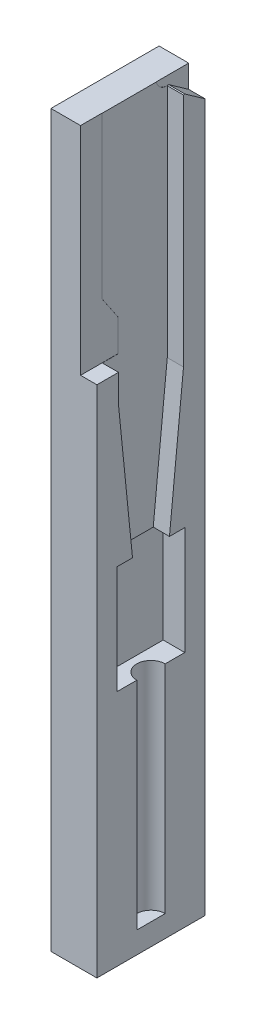
SolidWorks part; units mm, degrees
ref_plane "정면" through (0, 0, 0) normal (0, 0, 1) x (1, 0, 0)
ref_plane "윗면" through (0, 0, 0) normal (0, 1, 0) x (1, 0, 0)
ref_plane "우측면" through (0, 0, 0) normal (1, 0, 0) x (0, 0, -1)
sketch "스케치1" plane through (0, 0, 0) normal (1, 0, 0) x (0, 0, -1)
  line L0 (0, -135) -> (0, 0) construction
  line L1 (-20, -270) -> (20, -270)
  line L2 (-20, -270) -> (-20, 0)
  line L3 (-20, 0) -> (20, 0)
  line L4 (20, -270) -> (20, 0)
  line L5 (-20, -270) -> (20, 0) construction
  line L6 (-20, 0) -> (20, -270) construction
  point P0 (0, -135)
  dimension "D1" = 270
  dimension "D2" = 40
extrude "보스-돌출1" add sketch "스케치1" along normal mid plane 34
sketch "스케치2" plane through (0, 0, 0) normal (1, 0, 0) x (0, 0, -1)
  line L0 (-12.025, 0) -> (-12.025, -90.3198)
  line L1 (20, 0) -> (-20, 0) construction
  line L2 (-12.025, -90.3198) -> (-6, -150.3198)
  line L3 (-6, -150.3198) -> (6, -150.3198)
  line L4 (12.025, -90.3198) -> (6, -150.3198)
  line L5 (12.025, 0) -> (-12.025, 0)
  line L6 (0, 0) -> (0, -150.3198) construction
  line L7 (12.025, 0) -> (12.025, -90.3198)
  dimension "D1" = 12
  dimension "D2" = 24.05
  dimension "D3" = 60
extrude "컷-돌출1" cut sketch "스케치2" against normal mid plane 12
sketch "스케치3" plane through (0, 0, 0) normal (1, 0, 0) x (0, 0, -1)
  line L1 (-66.334, 26.0969) -> (85.9402, 26.0969)
  line L2 (-66.334, 26.0969) -> (-66.334, -328.7738)
  line L3 (-66.334, -328.7738) -> (85.9402, -328.7738)
  line L4 (85.9402, 26.0969) -> (85.9402, -328.7738)
extrude "컷-돌출2" cut sketch "스케치3" along normal through all contours L1 L4 L3 L2
ref_plane "평면1" through (0, -142, 0) normal (0, 1, 0) x (1, 0, 0)
sketch "스케치5" plane through (0, -142, 0) normal (0, 1, 0) x (1, 0, 0)
  line L1 (8, -12.5) -> (-8, -12.5)
  line L2 (8, -12.5) -> (8, 12.5)
  line L3 (8, 12.5) -> (-8, 12.5)
  line L4 (-8, -12.5) -> (-8, 12.5)
  line L5 (8, -12.5) -> (-8, 12.5) construction
  line L6 (8, 12.5) -> (-8, -12.5) construction
  point P0 (0, 0)
  dimension "D1" = 16
  dimension "D2" = 25
extrude "컷-돌출3" cut sketch "스케치5" against normal blind 40
sketch "스케치6" plane through (0, -142, 0) normal (0, 1, 0) x (1, 0, 0)
  circle A0 centre (0, 0) radius 5.25
  dimension "D1" = 10.5
extrude "컷-돌출4" cut sketch "스케치6" against normal blind 120
sketch "스케치7" plane through (0, 0, 0) normal (1, 0, 0) x (0, 0, -1)
  line L0 (-6.1559, -80) -> (-36.7141, -80)
  line L1 (-36.7141, -80) -> (-36.7141, 2.0427)
  line L2 (-36.7141, 2.0427) -> (-12.025, 2.0427)
  line L3 (-6.1559, -68.262) -> (-6.1559, -80)
  line L4 (-12.025, 2.0427) -> (-12.025, -59.5336)
  line L5 (-12.025, -90.3198) -> (-12.025, 0) construction
  line L6 (-12.025, -59.5336) -> (-6.1559, -68.262)
  line L7 (6.8907, 1.9547) -> (7.8972, 1.1819)
  line L8 (24.7897, -11.7879) -> (24.7897, 1.9547)
  line L9 (24.7897, 1.9547) -> (6.8907, 1.9547)
  line L10 (12.5764, -3.1721) -> (24.7897, -11.7879)
  arc A0 (7.8972, 1.1819) -> (12.5764, -3.1721) centre (11.9403, 0.8356) ccw
  dimension "D1" = 80
extrude "컷-돌출5" cut sketch "스케치7" against normal mid plane 12.1
